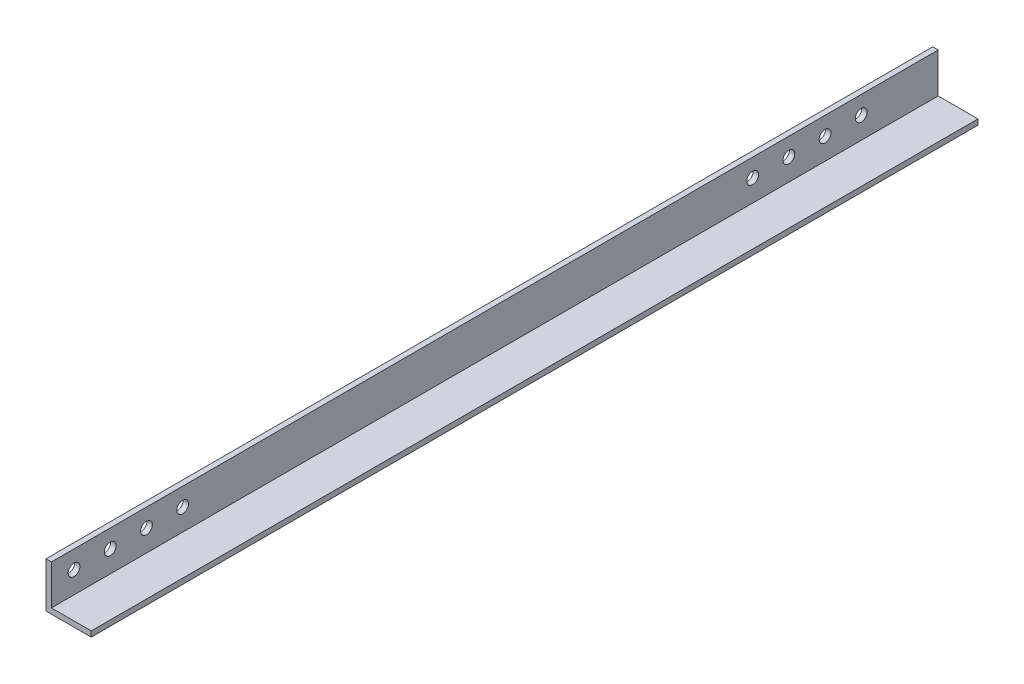
SolidWorks part; units mm, degrees
ref_plane "前视基准面" through (0, 0, 0) normal (0, 0, 1) x (1, 0, 0)
ref_plane "上视基准面" through (0, 0, 0) normal (0, 1, 0) x (1, 0, 0)
ref_plane "右视基准面" through (0, 0, 0) normal (1, 0, 0) x (0, 0, -1)
sketch "草图1" plane through (0, 0, 0) normal (0, 0, 1) x (1, 0, 0)
  line L1 (0, 0) -> (100, 0)
  line L2 (0, 0) -> (0, 100)
  line L3 (0, 100) -> (100, 100)
  line L4 (100, 0) -> (100, 100)
  dimension "D1" = 100
  dimension "D2" = 100
extrude "凸台-拉伸1" add sketch "草图1" along normal blind 1960
sketch "草图2" plane through (0, 0, 1960) normal (0, 0, 1) x (1, 0, 0)
  line L0 (0, 100) -> (0, 0) construction
  line L1 (100, 100) -> (12, 100)
  line L2 (100, 100) -> (100, 12)
  line L3 (100, 12) -> (12, 12)
  line L4 (12, 100) -> (12, 12)
  line L5 (0, 0) -> (100, 0) construction
  dimension "D1" = 12
  dimension "D2" = 12
extrude "切除-拉伸1" cut sketch "草图2" against normal through all
sketch "草图3" plane through (12, 0, 0) normal (1, 0, 0) x (0, 0, -1)
  line L0 (0, 100) -> (-1960, 100) construction
  line L1 (-1960, 100) -> (-1960, 12) construction
  circle A0 centre (-1910, 60) radius 13
  point P4 (-1960, 56)
  dimension "D1" = 26
  dimension "D2" = 40
  dimension "D3" = 50
extrude "切除-拉伸2" cut sketch "草图3" against normal through all
pattern_linear "阵列(线性)1" count 4 spacing 80 along (0, 0, -1) of "切除-拉伸2"
sketch "草图4" plane through (12, 0, 0) normal (1, 0, 0) x (0, 0, -1)
  line L0 (0, 100) -> (0, 12) construction
  line L1 (0, 100) -> (-1960, 100) construction
  circle A0 centre (-170, 60) radius 13
  dimension "D1" = 26
  dimension "D2" = 170
  dimension "D3" = 40
extrude "切除-拉伸3" cut sketch "草图4" against normal through all
pattern_linear "阵列(线性)2" count 4 spacing 80 along (0, 0, 1) of "切除-拉伸3"
